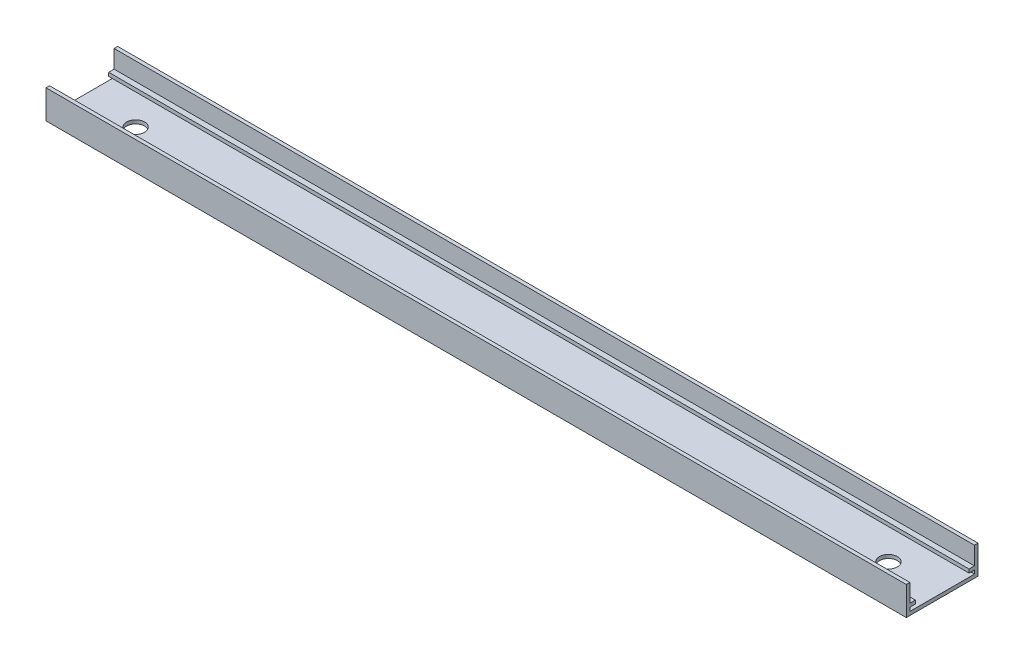
SolidWorks part; units mm, degrees
ref_plane "Front Plane" through (0, 0, 0) normal (0, 0, 1) x (1, 0, 0)
ref_plane "Top Plane" through (0, 0, 0) normal (0, 1, 0) x (1, 0, 0)
ref_plane "Right Plane" through (0, 0, 0) normal (1, 0, 0) x (0, 0, -1)
sketch "Sketch1" plane through (0, 0, 0) normal (1, 0, 0) x (0, 0, -1)
  line L0 (0, 0) -> (25.4, 0)
  line L1 (0, 0) -> (0, 10.16)
  line L2 (0, 10.16) -> (1.27, 10.16)
  line L3 (1.27, 10.16) -> (1.27, 3.81)
  line L4 (1.27, 3.81) -> (3.1759, 3.81)
  line L5 (3.1759, 3.81) -> (3.1759, 2.54)
  line L6 (3.1759, 2.54) -> (1.27, 2.54)
  line L7 (1.27, 2.54) -> (1.27, 1.27)
  line L8 (1.27, 1.27) -> (24.13, 1.27)
  line L10 (24.13, 2.54) -> (24.13, 1.27)
  line L11 (22.2241, 2.54) -> (24.13, 2.54)
  line L12 (22.2241, 3.81) -> (22.2241, 2.54)
  line L13 (24.13, 3.81) -> (22.2241, 3.81)
  line L14 (24.13, 10.16) -> (24.13, 3.81)
  line L15 (25.4, 10.16) -> (24.13, 10.16)
  line L16 (25.4, 0) -> (25.4, 10.16)
  dimension "D1" = 25.4
  dimension "D2" = 10.16
  dimension "D3" = 1.27
  dimension "D4" = 1.27
  dimension "D5" = 1.27
  dimension "D6" = 1.27
  dimension "D7" = 6.35
extrude "Boss-Extrude1" add sketch "Sketch1" against normal blind 304.8
sketch "Sketch2" plane through (0, 1.27, 0) normal (0, 1, 0) x (1, 0, 0)
  line L0 (-304.8, 12.7) -> (0, 12.7) construction
  line L1 (-304.8, 24.13) -> (-304.8, 1.27) construction
  line L2 (0, 24.13) -> (0, 1.27) construction
  line L3 (-152.4, 22.2241) -> (-152.4, 3.1759) construction
  line L4 (-304.8, 22.2241) -> (0, 22.2241) construction
  line L5 (-304.8, 3.1759) -> (0, 3.1759) construction
  circle A0 centre (-285.75, 12.7) radius 3.175
  circle A1 centre (-19.05, 12.7) radius 3.175
  dimension "D1" = 6.35
  dimension "D2" = 19.05
extrude "Cut-Extrude2" cut sketch "Sketch2" against normal through all
